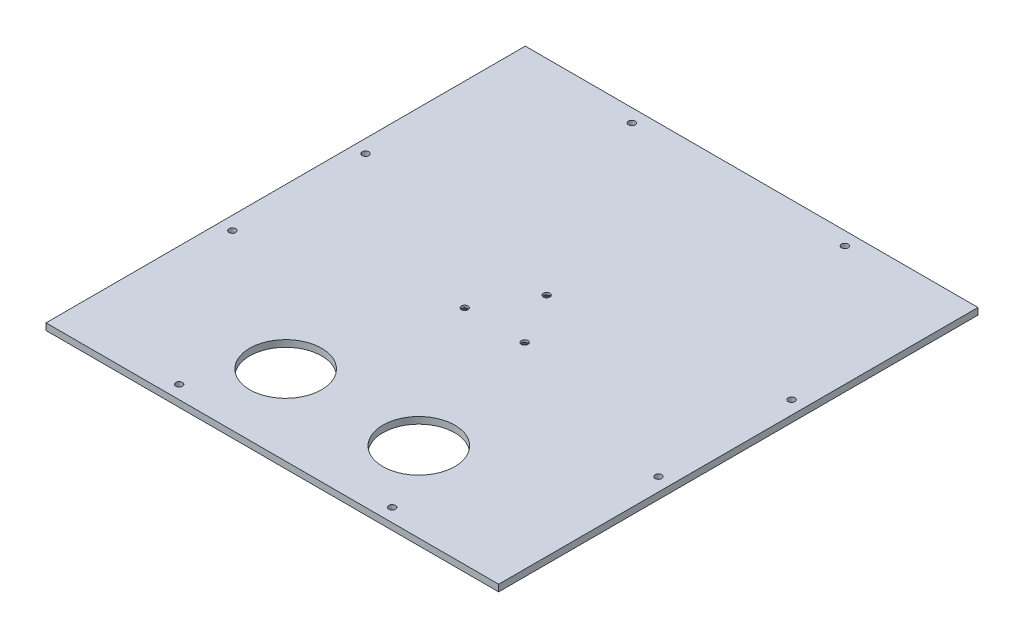
SolidWorks part; units mm, degrees
material "6061-T6 (SS)"
ref_plane "Front Plane" through (0, 0, 0) normal (0, 0, 1) x (1, 0, 0)
ref_plane "Top Plane" through (0, 0, 0) normal (0, 1, 0) x (1, 0, 0)
ref_plane "Right Plane" through (0, 0, 0) normal (1, 0, 0) x (0, 0, -1)
sketch "Sketch1" plane through (0, 0, 0) normal (0, 1, 0) x (1, 0, 0)
  line L1 (0, 0) -> (215.9, 0)
  line L2 (0, 0) -> (0, 228.6)
  line L3 (0, 228.6) -> (215.9, 228.6)
  line L4 (215.9, 0) -> (215.9, 228.6)
  dimension "D1" = 215.9
  dimension "D2" = 228.6
extrude "Boss-Extrude1" add sketch "Sketch1" along normal blind 3.175
sketch "Sketch2" plane through (0, 3.175, 0) normal (0, 1, 0) x (1, 0, 0)
  line L0 (139.7, 38.1) -> (76.2, 38.1) construction
  line L2 (139.7, 38.1) -> (215.9, 38.1) construction
  line L3 (215.9, 0) -> (215.9, 228.6) construction
  line L4 (76.2, 38.1) -> (0, 38.1) construction
  line L5 (0, 0) -> (215.9, 0) construction
  line L6 (0, 228.6) -> (0, 0) construction
  circle A0 centre (139.7, 38.1) radius 17.145
  circle A1 centre (76.2, 38.1) radius 17.145
  point P5 (215.9, 114.3)
  point P13 (107.95, 0)
  point P14 (107.95, 114.3)
  point P15 (-75.9559, 208.7303)
  dimension "D1" = 34.29
  dimension "D2" = 38.1
  dimension "D3" = 63.5
extrude "Cut-Extrude1" cut sketch "Sketch2" against normal through all
sketch "Sketch3" plane through (0, 3.175, 0) normal (0, 1, 0) x (1, 0, 0)
  line L0 (0, 228.6) -> (0, 0) construction
  line L1 (0, 0) -> (215.9, 0) construction
  circle A0 centre (107.95, 130.81) radius 1.5875
  circle A1 centre (122.2481, 106.045) radius 1.5875
  circle A2 centre (93.6519, 106.045) radius 1.5875
  point P0 (0, 114.3)
  point P1 (107.95, 0)
  point P4 (107.95, 114.3)
  dimension "D2" = 3.175
  dimension "D1" = 16.51
  dimension "D3" = 3
extrude "Cut-Extrude2" cut sketch "Sketch3" against normal through all
sketch "Sketch4" plane through (0, 3.175, 0) normal (0, 1, 0) x (1, 0, 0)
  line L0 (215.9, 228.6) -> (0, 228.6) construction
  line L1 (0, 228.6) -> (0, 0) construction
  line L2 (0, 0) -> (215.9, 0) construction
  line L3 (107.95, 228.6) -> (107.95, 0) construction
  circle A0 centre (6.35, 146.05) radius 1.5875
  circle A1 centre (6.35, 82.55) radius 1.5875
  circle A2 centre (57.15, 6.35) radius 1.5875
  circle A3 centre (57.15, 222.25) radius 1.5875
  circle A4 centre (158.75, 6.35) radius 1.5875
  circle A5 centre (209.55, 82.55) radius 1.5875
  circle A6 centre (209.55, 146.05) radius 1.5875
  circle A7 centre (158.75, 222.25) radius 1.5875
  point P14 (107.95, 0)
  point P15 (107.95, 228.6)
  dimension "D1" = 3.175
  dimension "D2" = 6.35
  dimension "D3" = 6.35
  dimension "D4" = 6.35
  dimension "D5" = 6.35
  dimension "D6" = 57.15
  dimension "D7" = 57.15
  dimension "D8" = 82.55
  dimension "D9" = 82.55
extrude "Cut-Extrude3" cut sketch "Sketch4" against normal through all
chamfer "Chamfer1" distance 2.1082 angle 41 3 edges at (93.6519, 0, -104.4575) (122.2481, 0, -104.4575) (107.95, 0, -129.2225)
sketch "Sketch5" plane through (0, 0, 0) normal (0, -1, 0) x (1, 0, 0)
  line L0 (215.9, -228.6) -> (0, -228.6) construction
  line L1 (95.25, -120.65) -> (19.05, -120.65)
  line L2 (95.25, -120.65) -> (95.25, -209.55)
  line L3 (95.25, -209.55) -> (19.05, -209.55)
  line L4 (19.05, -120.65) -> (19.05, -209.55)
  line L5 (0, -228.6) -> (0, 0) construction
  line L6 (107.95, -130.81) -> (107.95, -50130.81) construction
  line L7 (19.05, -95.25) -> (95.25, -95.25)
  line L9 (19.05, -69.85) -> (95.25, -69.85)
  line L10 (95.25, -95.25) -> (95.25, -69.85)
  line L11 (0, 0) -> (215.9, 0) construction
  line L13 (19.05, -95.25) -> (19.05, -19.05)
  line L14 (19.05, -19.05) -> (44.45, -19.05)
  line L15 (44.45, -95.25) -> (44.45, -19.05)
  line L16 (120.65, -209.55) -> (196.85, -209.55)
  line L17 (196.85, -120.65) -> (196.85, -209.55)
  line L18 (120.65, -120.65) -> (196.85, -120.65)
  line L19 (120.65, -120.65) -> (120.65, -209.55)
  line L20 (196.85, -69.85) -> (120.65, -69.85)
  line L21 (120.65, -95.25) -> (120.65, -69.85)
  line L22 (196.85, -95.25) -> (120.65, -95.25)
  line L24 (196.85, -19.05) -> (171.45, -19.05)
  line L25 (171.45, -95.25) -> (171.45, -19.05)
  line L27 (196.85, -95.25) -> (196.85, -19.05)
  circle A0 centre (76.2, -38.1) radius 17.145 construction
  point P8 (0, -114.3)
  dimension "D1" = 19.05
  dimension "D2" = 19.05
  dimension "D3" = 6.35
  dimension "D4" = 76.2
  dimension "D5" = 19.05
  dimension "D6" = 31.75
  dimension "D7" = 19.05
  dimension "D8" = 31.75
extrude "Cut-Extrude4" cut sketch "Sketch5" against normal blind 1.5875 contours L9 L15 L14 L13 | L7 L15 L9 L13 | L15 L7 L10 L9 | L1 L4 L3 L2 | L18 L19 L16 L17 | L22 L25 L20 L21 | L22 L27 L20 L25 | L20 L27 L24 L25
fillet "Fillet1" radius 3.175 18 edges at (19.05, 0.7937, -95.25) (95.25, 0.7937, -95.25) (95.25, 0.7937, -69.85) (44.45, 0.7937, -19.05) (19.05, 0.7937, -19.05) (196.85, 0.7937, -19.05) (196.85, 0.7937, -95.25) (171.45, 0.7937, -19.05) (120.65, 0.7937, -69.85) (120.65, 0.7937, -95.25) (196.85, 0.7937, -120.65) (120.65, 0.7937, -120.65) (120.65, 0.7937, -209.55) (196.85, 0.7937, -209.55) (95.25, 0.7937, -209.55) (95.25, 0.7937, -120.65) (19.05, 0.7937, -209.55) (19.05, 0.7937, -120.65)
fillet "Fillet2" radius 25.4 2 edges at (171.45, 0.7937, -69.85) (44.45, 0.7937, -69.85)
